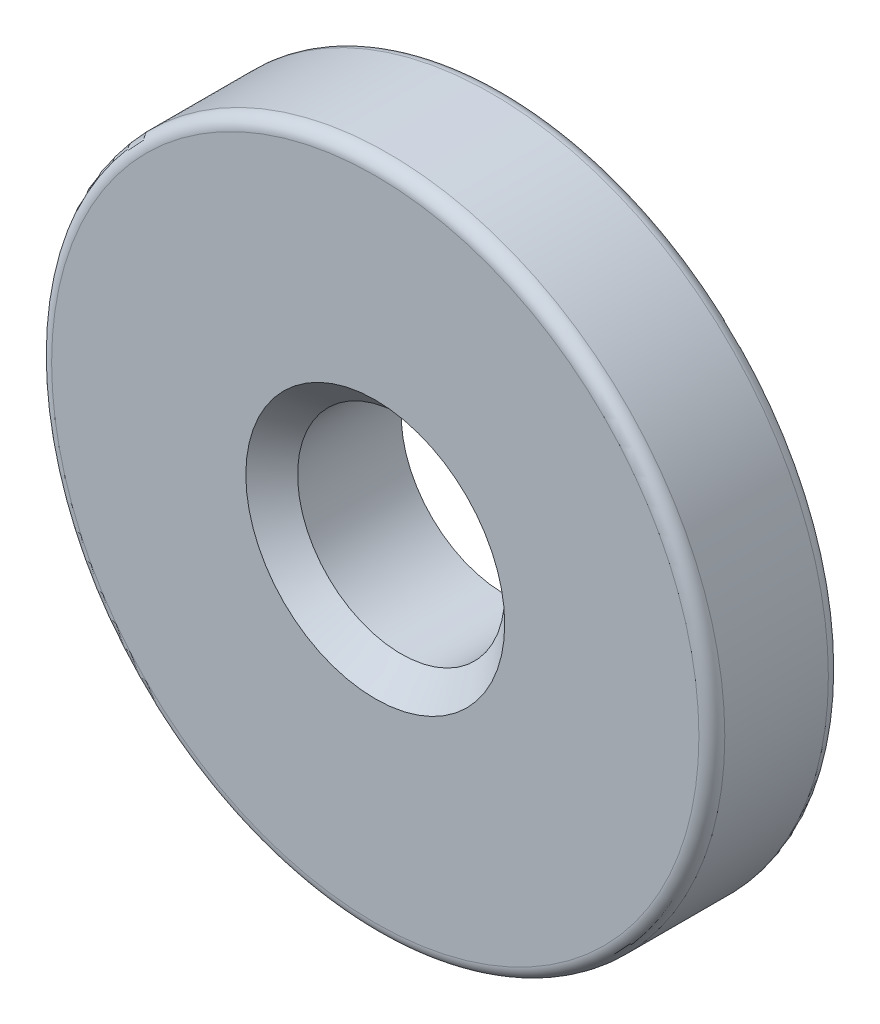
SolidWorks part; units mm, degrees
ref_plane "Front Plane" through (0, 0, 0) normal (1, 0, 0) x (0, 1, 0)
ref_plane "Top Plane" through (0, 0, 0) normal (0, 0, 1) x (0, 1, 0)
ref_plane "Right Plane" through (0, 0, 0) normal (0, 1, 0) x (-1, 0, 0)
sketch "Sketch1" plane through (0, 0, 0) normal (0, 0, 1) x (0, 1, 0)
  circle A0 centre (0, 0) radius 4
  circle A1 centre (0, 0) radius 13
  dimension "D1" = 8
  dimension "D2" = 26
extrude "Boss-Extrude1" add sketch "Sketch1" along normal blind 5
chamfer "Chamfer1" distance 1 angle 45 1 edges at (4, 0, 5)
fillet "Fillet1" radius 0.5 2 edges at (13, 0, 0) (13, 0, 5)
